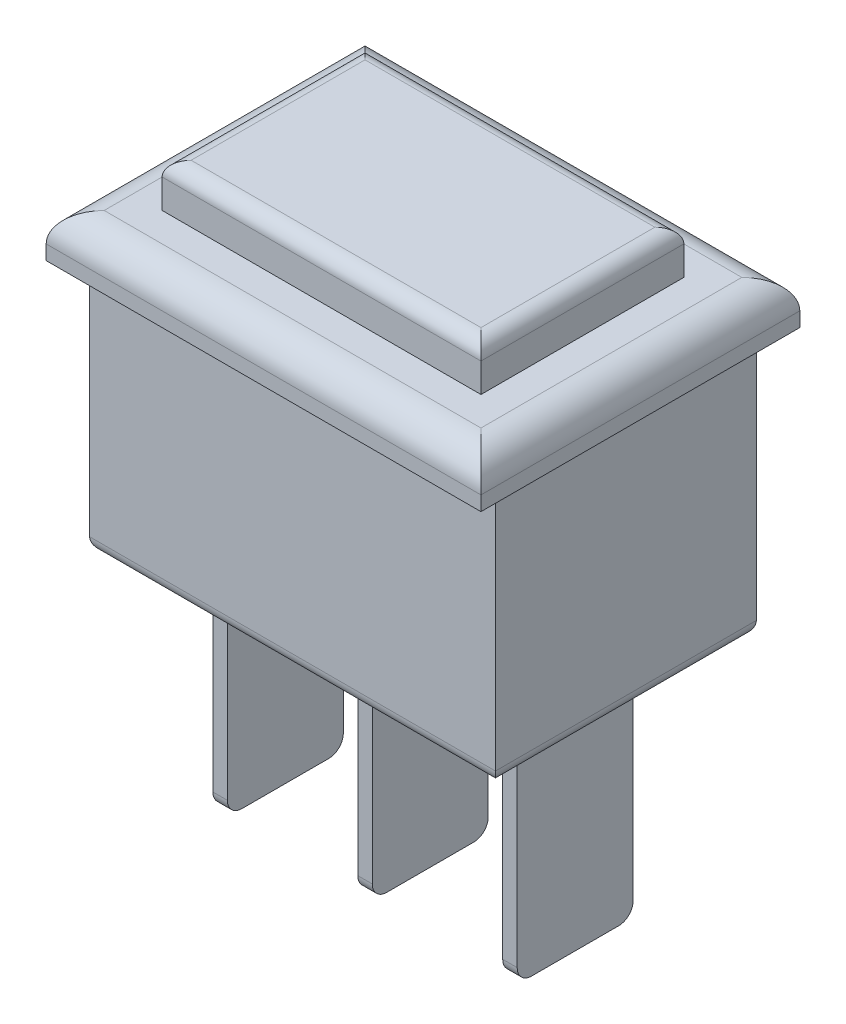
SolidWorks part; units mm, degrees
ref_plane "Спереди" through (0, 0, 0) normal (0, 0, 1) x (1, 0, 0)
ref_plane "Сверху" through (0, 0, 0) normal (0, 1, 0) x (1, 0, 0)
ref_plane "Справа" through (0, 0, 0) normal (1, 0, 0) x (0, 0, -1)
sketch "Эскиз1" plane through (0, 0, 0) normal (0, 1, 0) x (1, 0, 0)
  line L1 (-7, -4.5) -> (7, -4.5)
  line L2 (-7, -4.5) -> (-7, 4.5)
  line L3 (-7, 4.5) -> (7, 4.5)
  line L4 (7, -4.5) -> (7, 4.5)
  line L5 (-7, -4.5) -> (7, 4.5) construction
  line L6 (-7, 4.5) -> (7, -4.5) construction
  point P0 (0, 0)
  dimension "D1" = 14
  dimension "D2" = 9
extrude "Бобышка-Вытянуть1" add sketch "Эскиз1" along normal blind 9
sketch "Эскиз2" plane through (0, 9, 0) normal (0, 1, 0) x (1, 0, 0)
  line L1 (-7.5, -5.5) -> (7.5, -5.5)
  line L2 (-7.5, -5.5) -> (-7.5, 5.5)
  line L3 (-7.5, 5.5) -> (7.5, 5.5)
  line L4 (7.5, -5.5) -> (7.5, 5.5)
  line L5 (-7.5, -5.5) -> (7.5, 5.5) construction
  line L6 (-7.5, 5.5) -> (7.5, -5.5) construction
  point P0 (0, 0)
  dimension "D1" = 15
  dimension "D2" = 11
extrude "Бобышка-Вытянуть2" add sketch "Эскиз2" along normal blind 1.5
sketch "Эскиз3" plane through (0, 10.5, 0) normal (0, 1, 0) x (1, 0, 0)
  line L1 (-5.5, -3.5) -> (5.5, -3.5)
  line L2 (-5.5, -3.5) -> (-5.5, 3.5)
  line L3 (-5.5, 3.5) -> (5.5, 3.5)
  line L4 (5.5, -3.5) -> (5.5, 3.5)
  line L5 (-5.5, -3.5) -> (5.5, 3.5) construction
  line L6 (-5.5, 3.5) -> (5.5, -3.5) construction
  point P0 (0, 0)
  dimension "D1" = 11
  dimension "D2" = 7
extrude "Бобышка-Вытянуть3" add sketch "Эскиз3" along normal blind 1.5
sketch "Эскиз4" plane through (0, 0, 0) normal (0, -1, 0) x (1, 0, 0)
  line L0 (-1000, 0) -> (49000, 0) construction
  line L1 (4.75, 2) -> (5.25, 2)
  line L2 (-0.25, -2) -> (0.25, -2)
  line L3 (-0.25, -2) -> (-0.25, 2)
  line L4 (-0.25, 2) -> (0.25, 2)
  line L5 (0.25, -2) -> (0.25, 2)
  line L6 (-0.25, -2) -> (0.25, 2) construction
  line L7 (-0.25, 2) -> (0.25, -2) construction
  line L8 (5.25, -2) -> (5.25, 2)
  line L9 (4.75, -2) -> (5.25, 2) construction
  line L10 (4.75, -2) -> (4.75, 2)
  line L11 (4.75, 2) -> (5.25, -2) construction
  line L12 (4.75, -2) -> (5.25, -2)
  line L13 (-0.25, 2) -> (0.25, 2)
  line L14 (0.25, -2) -> (0.25, 2)
  line L15 (-0.25, -2) -> (0.25, 2) construction
  line L16 (-0.25, -2) -> (-0.25, 2)
  line L17 (-0.25, 2) -> (0.25, -2) construction
  line L18 (-0.25, -2) -> (0.25, -2)
  line L19 (-5.25, 2) -> (-4.75, 2)
  line L20 (-4.75, -2) -> (-4.75, 2)
  line L21 (-5.25, -2) -> (-4.75, 2) construction
  line L22 (-5.25, -2) -> (-5.25, 2)
  line L23 (-5.25, 2) -> (-4.75, -2) construction
  line L24 (-5.25, -2) -> (-4.75, -2)
  line L25 (-0.25, 2) -> (4.75, 2) construction
  point P1 (0, 0)
  point P9 (-5, 0)
  dimension "D1" = 0.5
  dimension "D2" = 4
  dimension "D5" = 5
  dimension "D6" = 5
  dimension "D3" = 2
  dimension "D4" = 2
extrude "Бобышка-Вытянуть4" add sketch "Эскиз4" along normal blind 8 contours L2 L5 L4 L3 | L10 L12 L8 L1 | L22 L24 L20 L19
fillet "Скругление1" radius 1 4 edges at (7.5, 10.5, 0) (0, 10.5, 5.5) (0, 10.5, -5.5) (-7.5, 10.5, 0)
fillet "Скругление2" radius 0.5 4 edges at (5.5, 12, 0) (0, 12, -3.5) (-5.5, 12, 0) (0, 12, 3.5)
fillet "Скругление3" radius 0.5 4 edges at (7, 0, 0) (0, 0, -4.5) (-7, 0, 0) (0, 0, 4.5)
fillet "Скругление4" radius 0.5 18 edges at (5, 0, -2) (4.75, 0, 0) (5, 0, 2) (5.25, 0, 0) (0, 0, 2) (-5, 0, -2) (-5, 0, 2) (0, 0, -2) (0.25, 0, 0) (-0.25, 0, 0) (-5.25, 0, 0) (-4.75, 0, 0) (-5, -8, 2) (-5, -8, -2) (0, -8, 2) (0, -8, -2) (5, -8, 2) (5, -8, -2)
